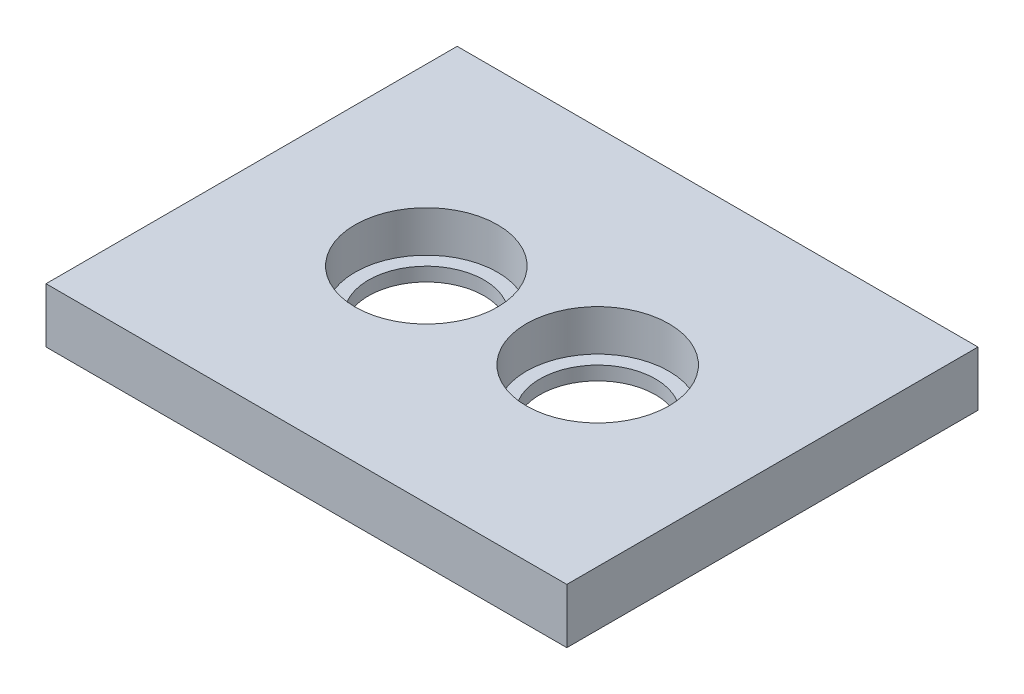
SolidWorks part; units mm, degrees
ref_plane "Ön Düzlem" through (0, 0, 0) normal (0, 0, 1) x (1, 0, 0)
ref_plane "Üst Düzlem" through (0, 0, 0) normal (0, 1, 0) x (1, 0, 0)
ref_plane "Sağ Düzlem" through (0, 0, 0) normal (1, 0, 0) x (0, 0, -1)
sketch "Sketch1" plane through (0, 0, 0) normal (0, 1, 0) x (1, 0, 0)
  line L1 (-95, -75) -> (95, -75)
  line L2 (-95, -75) -> (-95, 75)
  line L3 (-95, 75) -> (95, 75)
  line L4 (95, -75) -> (95, 75)
  line L5 (-95, -75) -> (95, 75) construction
  line L6 (-95, 75) -> (95, -75) construction
  point P0 (0, 0)
  dimension "D1" = 190
  dimension "D2" = 150
extrude "Boss-Extrude1" add sketch "Sketch1" along normal blind 20
sketch "Sketch2" plane through (0, 20, 0) normal (0, 1, 0) x (1, 0, 0)
  circle A0 centre (31.25, 0) radius 26
  circle A1 centre (-31.25, 0) radius 26
  dimension "D3" = 52
  dimension "D1" = 31.25
  dimension "D2" = 31.25
extrude "Cut-Extrude1" cut sketch "Sketch2" against normal up to next
sketch "Sketch7" plane through (0, 20, 0) normal (0, 1, 0) x (1, 0, 0)
  line L0 (-95, 75) -> (-95, -75) construction
  line L1 (95, 75) -> (-95, 75) construction
  line L2 (-95, -75) -> (95, -75) construction
  line L3 (95, -75) -> (95, 75) construction
  circle A0 centre (-70, 55) radius 3
  circle A1 centre (-70, -55) radius 3
  circle A2 centre (0, -55) radius 3
  circle A3 centre (0, 55) radius 3
  circle A4 centre (70, 55) radius 3
  circle A5 centre (70, -55) radius 3
  dimension "D1" = 6
  dimension "D2" = 25
  dimension "D3" = 20
  dimension "D4" = 20
  dimension "D5" = 25
sketch "Sketch8" plane through (0, 0, 0) normal (0, -1, 0) x (1, 0, 0)
  circle A0 centre (31.25, 0) radius 26 construction
  circle A1 centre (-31.25, 0) radius 26 construction
  circle A2 centre (31.25, 0) radius 26
  circle A3 centre (-31.25, 0) radius 26
  circle A4 centre (31.25, 0) radius 21.1
  circle A5 centre (-31.25, 0) radius 21.1
  dimension "D1" = 42.2
extrude "Boss-Extrude2" add sketch "Sketch8" against normal blind 5
